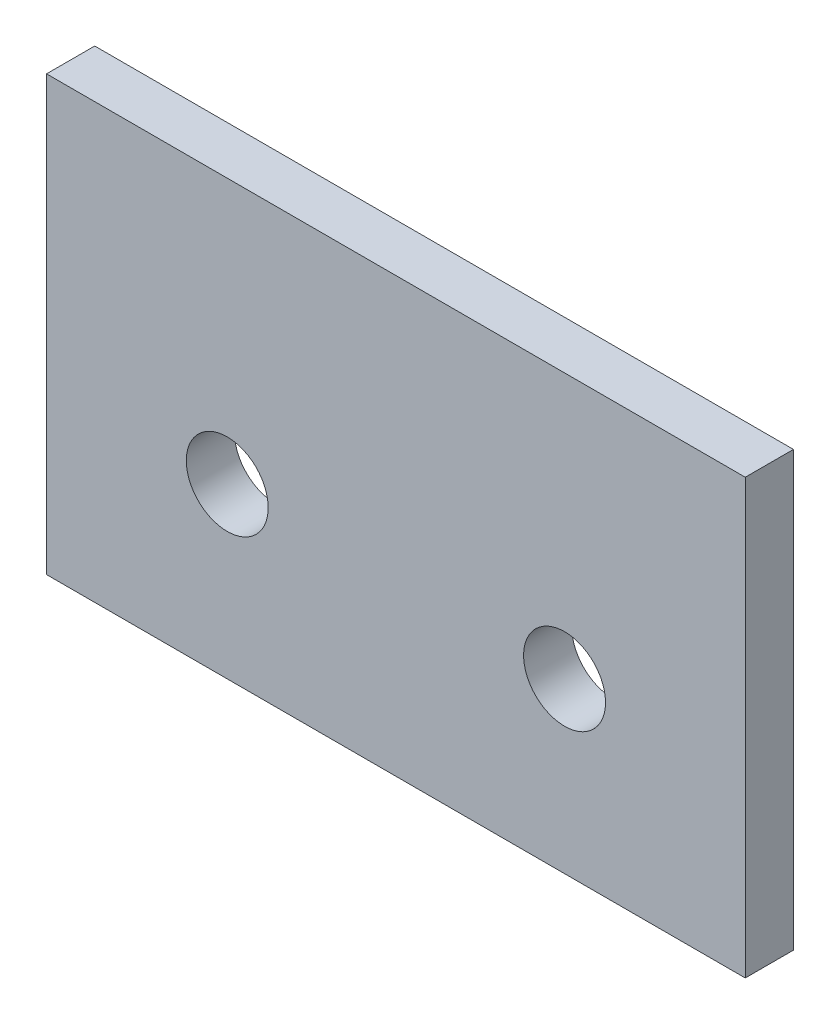
SolidWorks part; units mm, degrees
ref_plane "前视基准面" through (0, 0, 0) normal (0, 0, 1) x (1, 0, 0)
ref_plane "上视基准面" through (0, 0, 0) normal (0, 1, 0) x (1, 0, 0)
ref_plane "右视基准面" through (0, 0, 0) normal (1, 0, 0) x (0, 0, -1)
other "Configuration Table"
sketch "草图1" plane through (0, 0, 0) normal (0, 0, 1) x (1, 0, 0)
  line L0 (-17.8041, 7) -> (43.6885, 7) construction
  line L1 (0, 0) -> (29, 0)
  line L2 (0, 0) -> (0, 18)
  line L3 (0, 18) -> (29, 18)
  line L4 (29, 0) -> (29, 18)
  line L5 (14.5, 31.3774) -> (14.5, -6.4209) construction
  circle A0 centre (21.5, 7) radius 1.7
  circle A1 centre (7.5, 7) radius 1.7
  dimension "D4" = 3.4
  dimension "D1" = 7
  dimension "D2" = 11
  dimension "D3" = 29
  dimension "D5" = 14
extrude "凸台-拉伸1" add sketch "草图1" along normal blind 2
